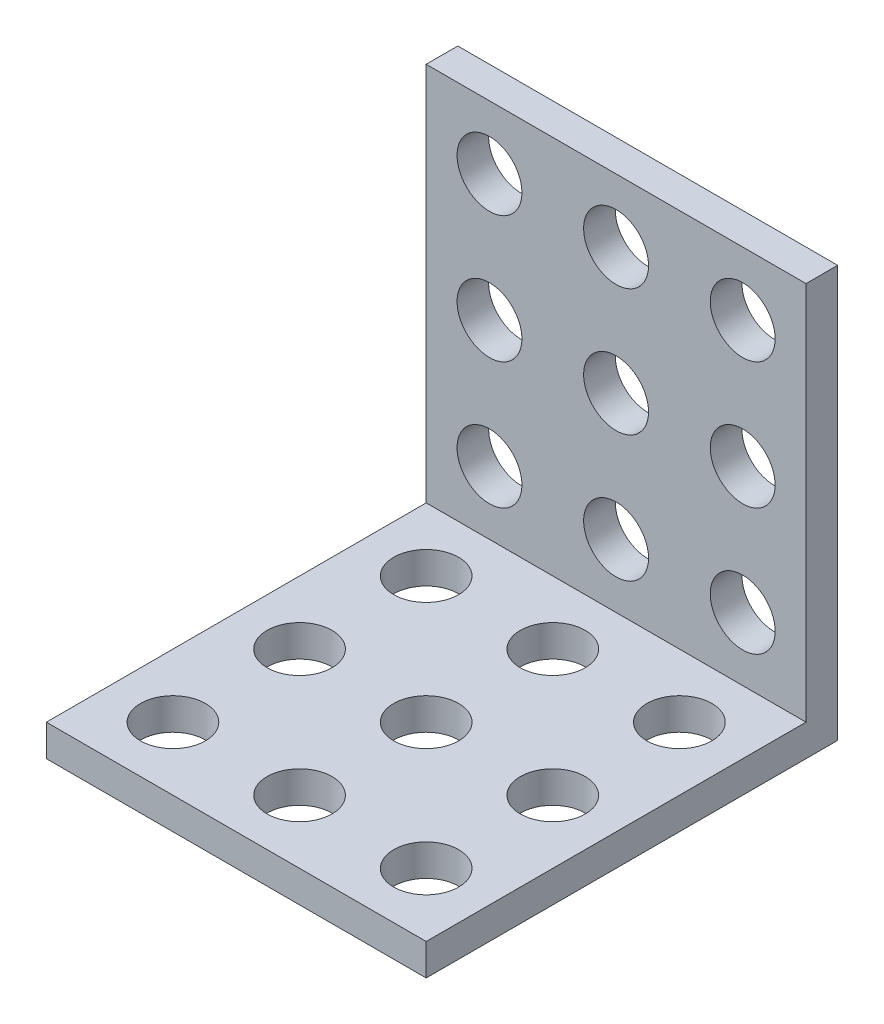
SolidWorks part; units mm, degrees
ref_plane "Front Plane" through (0, 0, 0) normal (0, 0, 1) x (1, 0, 0)
ref_plane "Top Plane" through (0, 0, 0) normal (0, 1, 0) x (1, 0, 0)
ref_plane "Right Plane" through (0, 0, 0) normal (1, 0, 0) x (0, 0, -1)
sketch "Sketch3" plane through (0, 0, 0) normal (1, 0, 0) x (0, 0, -1)
  line L0 (0, 0) -> (0, 26)
  line L1 (0, 0) -> (-26, 0)
  line L2 (-26, 0) -> (-26, 2)
  line L3 (0, 26) -> (-2, 26)
  line L4 (-26, 2) -> (-2, 2)
  line L5 (-2, 2) -> (-2, 26)
extrude "Boss-Extrude1" add sketch "Sketch3" along normal blind 24
hole_wizard "Ø4.1 (4.1) Diameter Hole1" positions "Sketch5" profile "Sketch4" hole size "Ø4.1" standard "ANSI Metric" end condition through all
sketch "Sketch5" plane through (0, 0, 2) normal (0, 0, 1) x (1, 0, 0)
  point P0 (4, 22)
sketch "Sketch4" plane through (4, 22, 2) normal (1, 0, 0) x (0, -1, 0)
  line L0 (0, 0) -> (0, 2)
  line L1 (0, 2) -> (2.05, 2)
  line L2 (2.05, 2) -> (2.05, 0)
  line L5 (2.05, 0) -> (0, 0)
  line L11 (0, -6.35) -> (0, 107.95) construction
  dimension "Thru Hole Dia." = 4.1
  dimension "Thru Hole Depth" = 2
pattern_linear "LPattern1" count 3 spacing 8 along (1, 0, 0) count 3 spacing 8 along (0, -1, 0) of "Ø4.1 (4.1) Diameter Hole1"
ref_plane "Mirroring Plane" through (0, 0, 0) normal (0, -0.7071, 0.7071) x (-1, 0, 0)
mirror "Mirror1" about plane through (0, 0, 0) normal (0, -0.7071, 0.7071) of "LPattern1", "Ø4.1 (4.1) Diameter Hole1"
